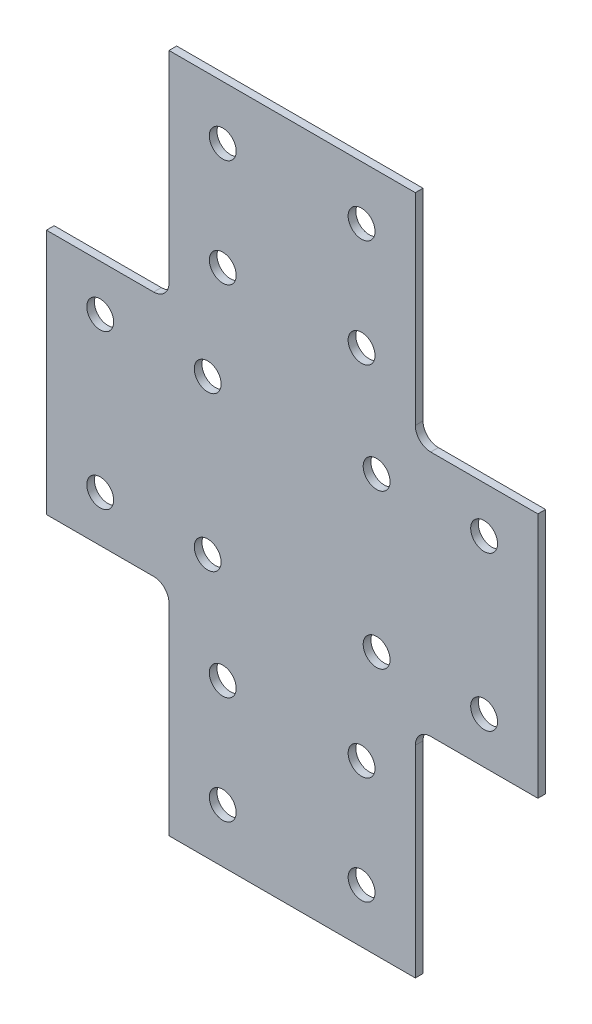
SolidWorks part; units mm, degrees
ref_plane "Front Plane" through (0, 0, 0) normal (0, 0, 1) x (1, 0, 0)
ref_plane "Top Plane" through (0, 0, 0) normal (0, 1, 0) x (1, 0, 0)
ref_plane "Right Plane" through (0, 0, 0) normal (1, 0, 0) x (0, 0, -1)
sketch "Sketch1" plane through (0, 0, 0) normal (0, 0, 1) x (1, 0, 0)
  line L0 (20.2074, -1520.6902) -> (20.2074, 1527.3098) construction
  line L1 (20.2074, 1349.5098) -> (-183.5006, 1349.5098)
  line L2 (-107.0466, 1528.8973) -> (-284.8466, 1732.6053) construction
  line L3 (20.2074, 1911.9928) -> (-183.5006, 1911.9928)
  line L4 (-284.8466, 1528.8973) -> (-107.0466, 1732.6053) construction
  line L5 (-183.5006, 4782.1928) -> (-183.5006, 1734.1928) construction
  line L6 (-183.5006, 1527.3098) -> (20.2074, 1527.3098) construction
  line L7 (20.2074, 1734.1928) -> (-183.5006, 1734.1928) construction
  line L8 (-139.0506, 1911.9928) -> (-139.0506, 1349.5098) construction
  line L9 (-81.6466, 1911.9928) -> (-81.6466, 1349.5098) construction
  line L10 (-107.0466, 1732.6053) -> (-3155.0466, 1732.6053) construction
  line L11 (121.5534, 1630.7513) -> (-284.8466, 1630.7513) construction
  line L12 (-183.5006, 1528.8973) -> (-284.8466, 1528.8973)
  line L13 (-107.0466, 1528.8973) -> (-3155.0466, 1528.8973) construction
  line L14 (-284.8466, 1528.8973) -> (-284.8466, 1732.6053)
  line L15 (-284.8466, 1732.6053) -> (-183.5006, 1732.6053)
  line L17 (121.5534, 1732.6053) -> (20.2074, 1732.6053)
  line L18 (121.5534, 1528.8973) -> (121.5534, 1732.6053)
  line L19 (20.2074, 1528.8973) -> (121.5534, 1528.8973)
  line L20 (20.2074, 1528.8973) -> (20.2074, 1349.5098)
  line L21 (-183.5006, 1349.5098) -> (-183.5006, 1528.8973)
  line L22 (20.2074, 1732.6053) -> (20.2074, 1911.9928)
  line L23 (-183.5006, 1732.6053) -> (-183.5006, 1911.9928)
  line L24 (-151.4966, 1694.5053) -> (-240.3966, 1694.5053) construction
  line L25 (-107.0466, 1613.6063) -> (-107.0466, 1528.8973) construction
  line L27 (-56.2466, 1732.6053) -> (-56.2466, 1528.8973) construction
  line L28 (121.5534, 1528.8973) -> (-56.2466, 1732.6053) construction
  line L29 (121.5534, 1732.6053) -> (-56.2466, 1528.8973) construction
  line L30 (77.1034, 1566.9973) -> (-11.7966, 1566.9973) construction
  line L31 (77.1034, 1694.5053) -> (-11.7966, 1694.5053) construction
  line L32 (32.6534, 1566.9973) -> (32.6534, 1694.5053) construction
  line L33 (-151.4966, 1566.9973) -> (-240.3966, 1566.9973) construction
  line L34 (-195.9466, 1566.9973) -> (-195.9466, 1694.5053) construction
  circle A0 centre (-139.0506, 1867.5428) radius 11.1125
  circle A1 centre (-151.4966, 1694.5053) radius 11.1125
  circle A2 centre (-11.7966, 1694.5053) radius 11.1125
  circle A3 centre (-24.2426, 1867.5428) radius 11.1125
  circle A4 centre (-24.2426, 1393.9598) radius 11.1125
  circle A5 centre (-139.0506, 1393.9598) radius 11.1125
  circle A6 centre (-151.4966, 1566.9973) radius 11.1125
  circle A7 centre (-11.7966, 1566.9973) radius 11.1125
  circle A8 centre (-240.3966, 1694.5053) radius 11.1125
  circle A9 centre (-139.0506, 1778.6428) radius 11.1125
  circle A10 centre (-139.0506, 1482.8598) radius 11.1125
  circle A11 centre (-240.3966, 1566.9973) radius 11.1125
  circle A12 centre (-24.2426, 1778.6428) radius 11.1125
  circle A13 centre (77.1034, 1694.5053) radius 11.1125
  circle A14 centre (77.1034, 1566.9973) radius 11.1125
  circle A15 centre (-24.2426, 1482.8598) radius 11.1125
  point P77 (32.6534, 1630.7513)
  point P79 (-195.9466, 1630.7513)
  dimension "D4" = 44.45
  dimension "D6" = 22.225
  dimension "D1" = 177.8
  dimension "D2" = 177.8
  dimension "D3" = 44.45
  dimension "D5" = 38.1
  dimension "D7" = 177.8
  dimension "D8" = 88.9
  dimension "D9" = 88.9
  dimension "D10" = 177.8
extrude "Boss-Extrude1" add sketch "Sketch1" along normal blind 6.35
fillet "Fillet1" radius 12.7 4 edges at (-183.5006, 1528.8973, 3.175) (-183.5006, 1732.6053, 3.175) (20.2074, 1732.6053, 3.175) (20.2074, 1528.8973, 3.175)
